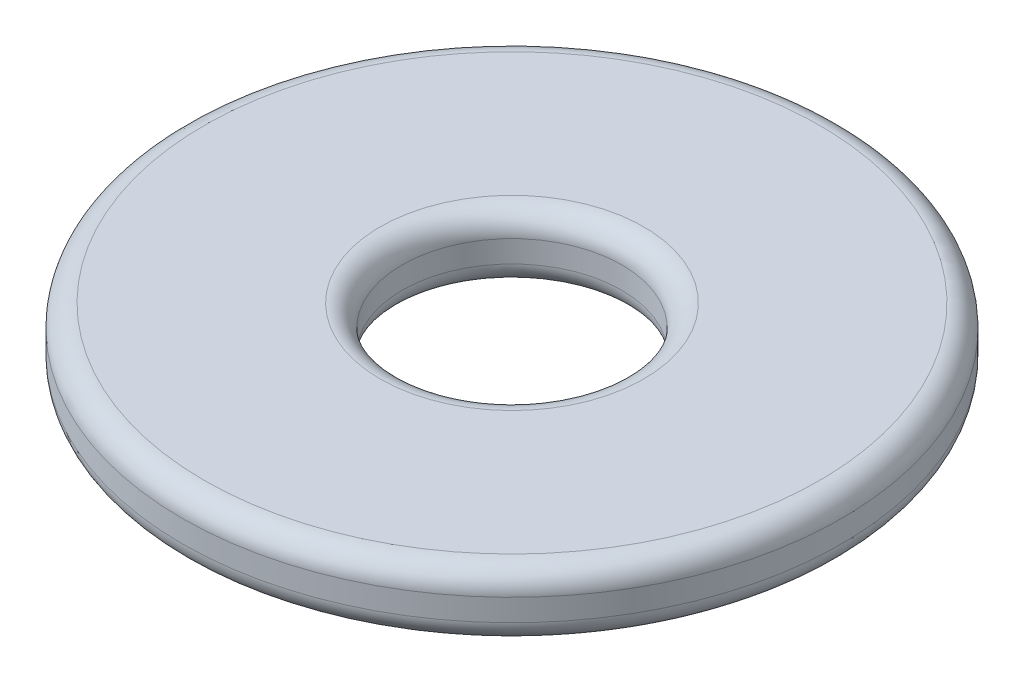
SolidWorks part; units mm, degrees
material "Cast Carbon Steel"
ref_plane "Front Plane" through (0, 0, 0) normal (0, 0, 1) x (1, 0, 0)
ref_plane "Top Plane" through (0, 0, 0) normal (0, 1, 0) x (1, 0, 0)
ref_plane "Right Plane" through (0, 0, 0) normal (1, 0, 0) x (0, 0, -1)
sketch "Sketch1" plane through (0, 0, 0) normal (0, 1, 0) x (1, 0, 0)
  circle A0 centre (0, 0) radius 6
  circle A1 centre (0, 0) radius 2
  dimension "D1" = 4
  dimension "D2" = 12
extrude "Boss-Extrude1" add sketch "Sketch1" along normal blind 1.2
fillet "Fillet1" radius 0.4 4 edges at (0, 0, 6) (0, 1.2, 6) (0, 0, 2) (0, 1.2, 2)
